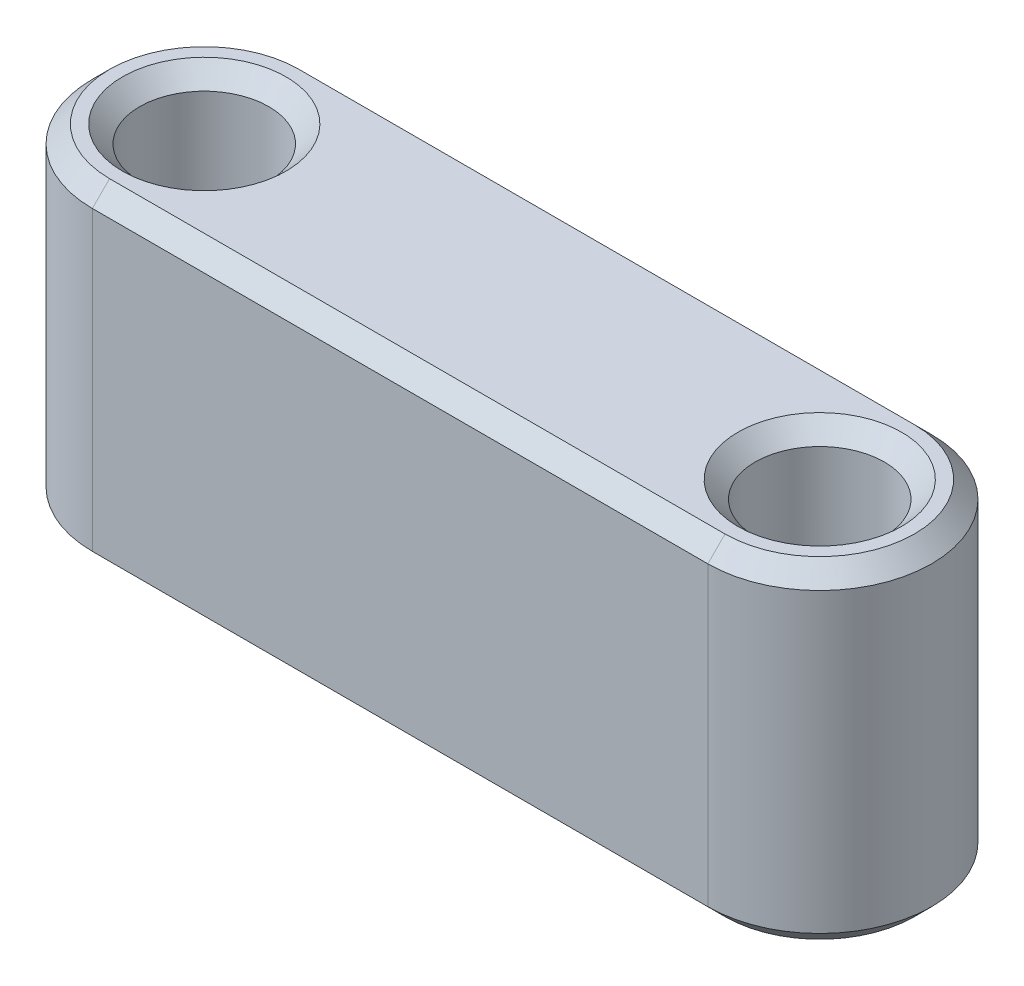
SolidWorks part; units mm, degrees
ref_plane "Front Plane" through (0, 0, 0) normal (0, 0, 1) x (1, 0, 0)
ref_plane "Top Plane" through (0, 0, 0) normal (0, 1, 0) x (1, 0, 0)
ref_plane "Right Plane" through (0, 0, 0) normal (1, 0, 0) x (0, 0, -1)
sketch "Sketch1" plane through (0, 0, 0) normal (0, 1, 0) x (1, 0, 0)
  line L0 (-12.6482, 0) -> (16.163, 0) construction
  line L1 (-5.9636, 0) -> (8.3364, 0) construction
  line L2 (-5.9636, 2.6) -> (8.3364, 2.6)
  line L3 (-5.9636, -2.6) -> (8.3364, -2.6)
  line L4 (1.1864, 6.0366) -> (1.1864, -10.7593) construction
  arc A0 (-5.9636, 2.6) -> (-5.9636, -2.6) centre (-5.9636, 0) ccw
  arc A1 (8.3364, -2.6) -> (8.3364, 2.6) centre (8.3364, 0) ccw
  circle A2 centre (-5.9636, 0) radius 1.5
  circle A4 centre (8.3364, 0) radius 1.5
  point P5 (1.1864, 0)
  point P10 (-8.5636, 0)
  point P11 (10.9364, 0)
  dimension "D3" = 3
  dimension "D1" = 19.5
  dimension "D2" = 5.2
extrude "Boss-Extrude1" add sketch "Sketch1" along normal mid plane 7.7
chamfer "Chamfer2" distance 0.4 angle 45 12 edges at (8.3364, -3.85, -1.5) (-5.9636, -3.85, 1.5) (1.1864, -3.85, 2.6) (10.9364, -3.85, 0) (-8.5636, -3.85, 0) (1.1864, -3.85, -2.6) (8.3364, 3.85, -1.5) (-5.9636, 3.85, 1.5) (10.9364, 3.85, 0) (1.1864, 3.85, 2.6) (-8.5636, 3.85, 0) (1.1864, 3.85, -2.6)
